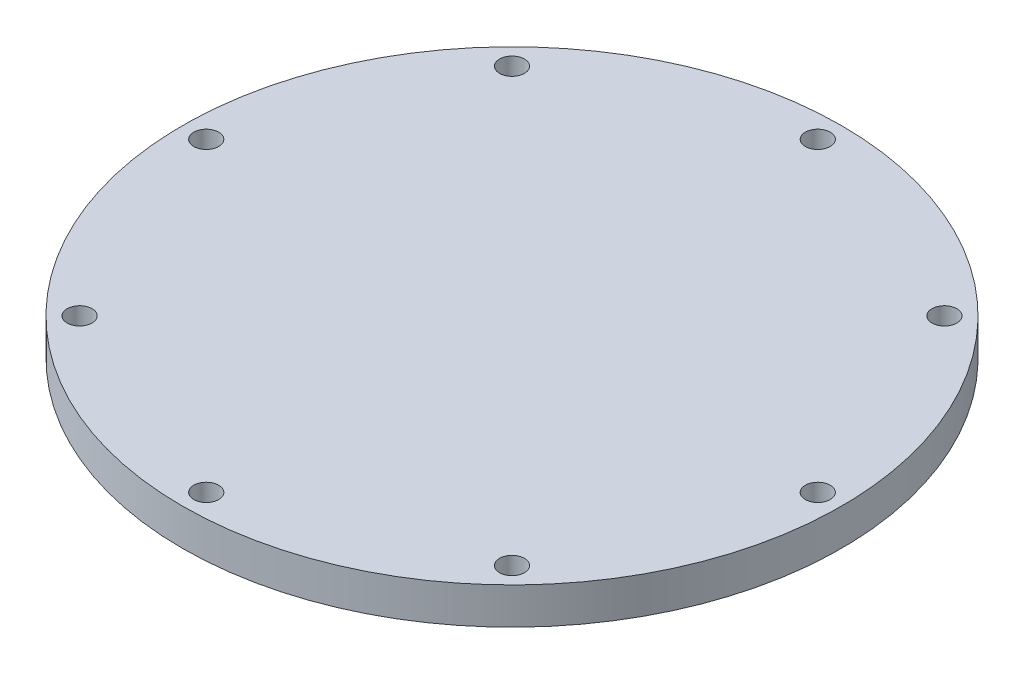
SolidWorks part; units mm, degrees
material "6061-T6 (SS)"
ref_plane "Front Plane" through (0, 0, 0) normal (0, 0, 1) x (1, 0, 0)
ref_plane "Top Plane" through (0, 0, 0) normal (0, 1, 0) x (1, 0, 0)
ref_plane "Right Plane" through (0, 0, 0) normal (1, 0, 0) x (0, 0, -1)
sketch "Sketch1" plane through (0, 0, 0) normal (0, 1, 0) x (1, 0, 0)
  circle A0 centre (0, 0) radius 45
  circle A1 centre (0, 41.75) radius 1.5
  circle A2 centre (29.5217, 29.5217) radius 1.5
  circle A3 centre (41.75, 0) radius 1.5
  circle A4 centre (29.5217, -29.5217) radius 1.5
  circle A5 centre (0, -41.75) radius 1.5
  circle A6 centre (-29.5217, -29.5217) radius 1.5
  circle A7 centre (-41.75, 0) radius 1.5
  circle A8 centre (-29.5217, 29.5217) radius 1.5
  point P22 (0, 0)
  dimension "D1" = 8
extrude "Boss-Extrude2" add sketch "Sketch1" along normal blind 5
sketch "Sketch9" plane through (0, 0, 0) normal (0, -1, 0) x (1, 0, 0)
  circle A2 centre (27, 0) radius 3.937
  circle A3 centre (0, -27) radius 3.937
  circle A4 centre (-27, 0) radius 3.937
  circle A5 centre (0, 27) radius 3.937
  point P15 (0, 0)
  dimension "D1" = 4
extrude "Boss-Extrude7" add sketch "Sketch9" along normal blind 4
sketch "Sketch10" plane through (0, 5, 0) normal (0, 1, 0) x (1, 0, 0)
  circle A0 centre (0, 41.75) radius 1.7
  circle A1 centre (29.5217, 29.5217) radius 1.7
  circle A2 centre (41.75, 0) radius 1.7
  circle A3 centre (29.5217, -29.5217) radius 1.7
  circle A4 centre (0, -41.75) radius 1.7
  circle A5 centre (-29.5217, -29.5217) radius 1.7
  circle A6 centre (-41.75, 0) radius 1.7
  circle A7 centre (-29.5217, 29.5217) radius 1.7
  point P19 (0, 0)
  dimension "D1" = 8
extrude "Cut-Extrude9" cut sketch "Sketch10" against normal blind 14
sketch "Sketch14" plane through (0, -4, 0) normal (0, -1, 0) x (1, 0, 0)
  point P0 (0, 27)
  point P1 (27, 0)
  point P3 (0, -27)
  point P5 (-27, 0)
hole_wizard "M3 Tapped Hole1" positions "Sketch14" profile "Sketch15" tap size "M3" standard "DIN"
sketch "Sketch15" plane through (0, -4, 27) normal (1, 0, 0) x (0, 0, -1)
  line L0 (0, 0) -> (0, 7.7511)
  line L1 (0, 7.7511) -> (1.25, 7)
  line L2 (1.25, 7) -> (1.25, 0)
  line L5 (1.25, 0) -> (0, 0)
  line L10 (0, 7.7511) -> (-1.25, 7) construction
  line L11 (0, -6.35) -> (0, 107.95) construction
  dimension "Tap Drill Dia." = 2.5
  dimension "Tap Drill Depth" = 7
  dimension "Drill Angle" = 118
cosmetic thread "Hole Thread1" parameters "D1"=10, "D2"=3
cosmetic thread "Hole Thread2" parameters "D1"=10, "D2"=3
cosmetic thread "Hole Thread3" parameters "D1"=10, "D2"=3
cosmetic thread "Hole Thread4" parameters "D1"=10, "D2"=3
